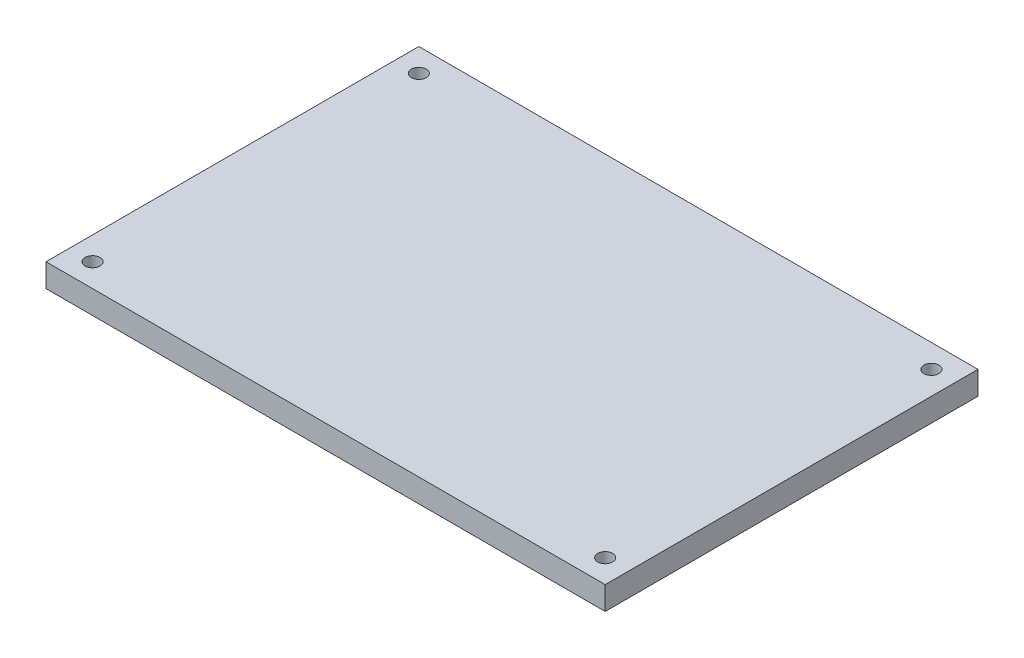
SolidWorks part; units mm, degrees
ref_plane "Plan de face" through (0, 0, 0) normal (0, 0, 1) x (1, 0, 0)
ref_plane "Plan de dessus" through (0, 0, 0) normal (0, 1, 0) x (1, 0, 0)
ref_plane "Plan de droite" through (0, 0, 0) normal (1, 0, 0) x (0, 0, -1)
sketch "Esquisse1" plane through (0, 0, 0) normal (0, 1, 0) x (1, 0, 0)
  line L1 (0, 0) -> (120, 0)
  line L2 (0, 0) -> (0, 80)
  line L3 (0, 80) -> (120, 80)
  line L4 (120, 0) -> (120, 80)
  dimension "D1" = 120
  dimension "D2" = 80
extrude "Boss.-Extru.1" add sketch "Esquisse1" along normal blind 5
sketch "Esquisse2" plane through (0, 0, 0) normal (0, 1, 0) x (1, 0, 0)
  line L0 (60, 80) -> (60, 0) construction
  line L1 (120, 80) -> (0, 80) construction
  line L2 (0, 0) -> (120, 0) construction
  line L3 (0, 40) -> (120, 40) construction
  line L4 (0, 80) -> (0, 0) construction
  line L5 (120, 0) -> (120, 80) construction
  circle A0 centre (5, 75) radius 1.6
  circle A1 centre (115, 75) radius 1.6
  circle A2 centre (115, 5) radius 1.6
  circle A3 centre (5, 5) radius 1.6
  point P14 (0, 0)
  dimension "D1" = 3.2
  dimension "D2" = 5
  dimension "D3" = 5
extrude "Enlèv. mat.-Extru.3" cut sketch "Esquisse2" along normal blind 10
